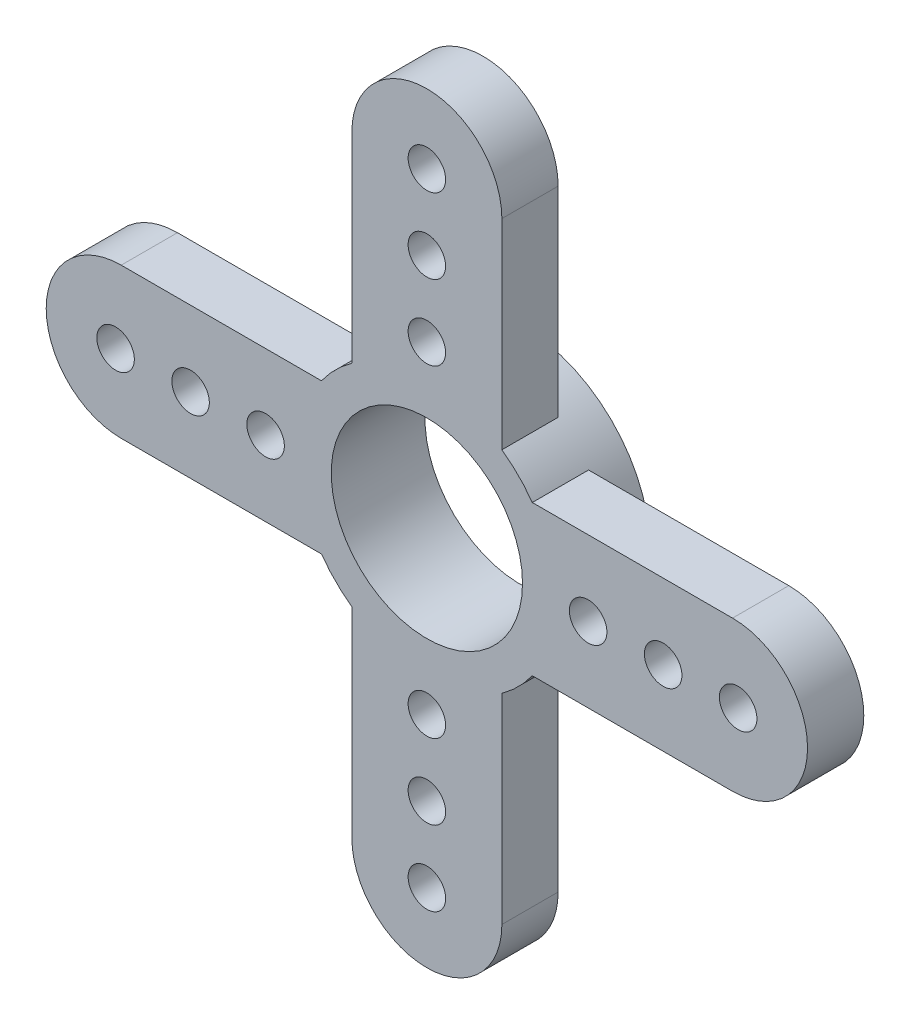
SolidWorks part; units mm, degrees
ref_plane "Front Plane" through (0, 0, 0) normal (0, 0, 1) x (1, 0, 0)
ref_plane "Top Plane" through (0, 0, 0) normal (0, 1, 0) x (1, 0, 0)
ref_plane "Right Plane" through (0, 0, 0) normal (1, 0, 0) x (0, 0, -1)
sketch "Compact_horn_center_OD6p9_profile" plane through (0, 0, 0) normal (0, 0, 1) x (1, 0, 0)
  circle A0 centre (0, 0) radius 3.45
  dimension "D1" = 6.9
extrude "Compact_horn_center_OD6p9" add sketch "Compact_horn_center_OD6p9_profile" along normal blind 1.5
sketch "Horizontal_blades_assumed_width4_profile" plane through (0, 0, 0) normal (0, 0, 1) x (1, 0, 0)
  line L1 (-8.15, -2) -> (8.15, -2)
  line L2 (-8.15, -2) -> (-8.15, 2)
  line L3 (-8.15, 2) -> (8.15, 2)
  line L4 (8.15, -2) -> (8.15, 2)
  dimension "D1" = 16.3
  dimension "D2" = 4
extrude "Horizontal_blades_assumed_width4" add sketch "Horizontal_blades_assumed_width4_profile" along normal blind 1.5
sketch "Vertical_blades_assumed_width4_profile" plane through (0, 0, 0) normal (0, 0, 1) x (1, 0, 0)
  line L1 (-2, -8.15) -> (2, -8.15)
  line L2 (-2, -8.15) -> (-2, 8.15)
  line L3 (-2, 8.15) -> (2, 8.15)
  line L4 (2, -8.15) -> (2, 8.15)
  dimension "D1" = 4
  dimension "D2" = 16.3
extrude "Vertical_blades_assumed_width4" add sketch "Vertical_blades_assumed_width4_profile" along normal blind 1.5
sketch "Rounded_blade_tips" plane through (0, 0, 0) normal (0, 0, 1) x (1, 0, 0)
  circle A0 centre (8.15, 0) radius 2
  circle A1 centre (-8.15, 0) radius 2
  circle A2 centre (0, 8.15) radius 2
  circle A3 centre (0, -8.15) radius 2
  dimension "D1" = 4
  dimension "D2" = 4
  dimension "D3" = 4
  dimension "D4" = 4
extrude "Rounded_tips_span20p3" add sketch "Rounded_blade_tips" along normal blind 1.5
sketch "Hub_total_height2p5_profile" plane through (0, 0, 0) normal (0, 0, 1) x (1, 0, 0)
  circle A0 centre (0, 0) radius 3.45
  dimension "D1" = 6.9
extrude "Hub_total_height2p5" add sketch "Hub_total_height2p5_profile" along normal blind 1 from offset 1
sketch "Purchased_spline_internals_omitted_profile" plane through (0, 0, 0) normal (0, 0, 1) x (1, 0, 0)
  circle A0 centre (0, 0) radius 2.55
  dimension "D1" = 5.1
extrude "Purchased_spline_internals_omitted" cut sketch "Purchased_spline_internals_omitted_profile" along normal through all from offset 50
sketch "Unmodified_stock_pilot_holes_profile" plane through (0, 0, 0) normal (0, 0, 1) x (1, 0, 0)
  circle A0 centre (-8.3, 0) radius 0.5
  circle A1 centre (-6.3, 0) radius 0.5
  circle A2 centre (-4.3, 0) radius 0.5
  circle A3 centre (4.3, 0) radius 0.5
  circle A4 centre (6.3, 0) radius 0.5
  circle A5 centre (8.3, 0) radius 0.5
  circle A6 centre (0, -8.3) radius 0.5
  circle A7 centre (0, -6.3) radius 0.5
  circle A8 centre (0, -4.3) radius 0.5
  circle A9 centre (0, 4.3) radius 0.5
  circle A10 centre (0, 6.3) radius 0.5
  circle A11 centre (0, 8.3) radius 0.5
  dimension "D1" = 1
  dimension "D2" = 1
  dimension "D3" = 1
  dimension "D4" = 1
  dimension "D5" = 1
  dimension "D6" = 1
  dimension "D7" = 1
  dimension "D8" = 1
  dimension "D9" = 1
  dimension "D10" = 1
  dimension "D11" = 1
  dimension "D12" = 1
extrude "Unmodified_stock_pilot_holes" cut sketch "Unmodified_stock_pilot_holes_profile" along normal through all from offset 50
